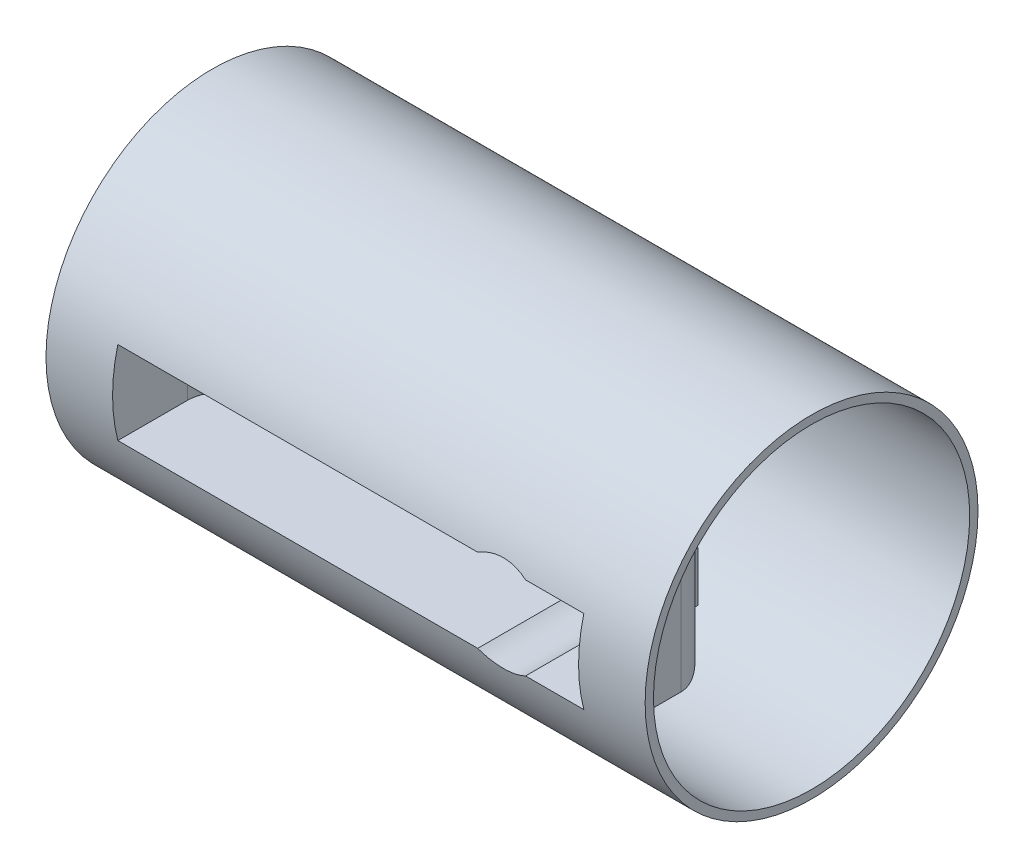
SolidWorks part; units mm, degrees
material "ABS PC"
ref_plane "前视" through (0, 0, 0) normal (0, 0, 1) x (1, 0, 0)
ref_plane "上视" through (0, 0, 0) normal (0, 1, 0) x (1, 0, 0)
ref_plane "右视" through (0, 0, 0) normal (1, 0, 0) x (0, 0, -1)
sketch "草图1" plane through (0, 0, 0) normal (0, 1, 0) x (1, 0, 0)
  line L1 (0, 0) -> (-300, 0)
  line L2 (0, 0) -> (0, -100)
  line L3 (0, -100) -> (-300, -100)
  line L4 (-300, 0) -> (-300, -100)
revolve "旋转1" add sketch "草图1" angle 360 about L1
sketch "草图2" plane through (0, 0, 0) normal (1, 0, 0) x (0, 0, -1)
  circle A0 centre (0, 0) radius 95
extrude "切除-拉伸1" cut sketch "草图2" against normal through all
sketch "草图5" plane through (0, 0, 0) normal (1, 0, 0) x (0, 0, -1)
  circle A0 centre (0, 0) radius 95
  circle A1 centre (0, 0) radius 100
extrude "凸台-拉伸1" add sketch "草图5" along normal blind 60
ref_plane "基准面1" through (0, 0, 100) normal (0, 0, 1) x (1, 0, 0)
sketch "草图6" plane through (0, 0, 100) normal (0, 0, 1) x (1, 0, 0)
  line L0 (60, -100) -> (60, 100) construction
  line L1 (20, 25) -> (-260, 25)
  line L2 (20, 25) -> (20, -25)
  line L3 (20, -25) -> (-260, -25)
  line L4 (-260, 25) -> (-260, -25)
  line L5 (-300, 100) -> (-300, -100) construction
  line L6 (60, 100) -> (-300, 100) construction
  line L7 (-300, -100) -> (60, -100) construction
  dimension "D1" = 40
  dimension "D2" = 40
  dimension "D3" = 75
  dimension "D4" = 75
  dimension "D5" = 50
extrude "切除-拉伸2" cut sketch "草图6" against normal blind 10
sketch "草图9" plane through (20, 0, 0) normal (-1, 0, 0) x (0, 0, 1)
  line L1 (88.3176, 35) -> (88.3176, -35)
  arc A1 (88.3176, -35) -> (88.3176, 35) centre (0, 0) ccw
extrude "凸台-拉伸3" add sketch "草图9" against normal blind 10 and the other way blind 290
sketch "草图14" plane through (0, 0, 88.3176) normal (0, 0, -1) x (-1, 0, 0)
  line L1 (270, -35) -> (-30, -35)
  line L2 (270, -35) -> (270, 35)
  line L3 (270, 35) -> (-30, 35)
  line L4 (-30, -35) -> (-30, 35)
extrude "凸台-拉伸5" add sketch "草图14" along normal blind 60
sketch "草图13" plane through (0, 0, 100) normal (0, 0, 1) x (1, 0, 0)
  line L1 (-260, 25) -> (20, 25)
  line L2 (-260, 25) -> (-260, -25)
  line L3 (-260, -25) -> (20, -25)
  line L4 (20, 25) -> (20, -25)
extrude "切除-拉伸3" cut sketch "草图13" against normal blind 65
fillet "圆角1" radius 20 6 edges at (-120, -35, 28.3176) (30, 0, 28.3176) (-120, 35, 28.3176) (-270, 0, 28.3176) (-260, 0, 35) (20, 0, 35)
sketch "草图15" plane through (0, 0, 28.3176) normal (0, 0, -1) x (-1, 0, 0)
  line L0 (-10, 15) -> (-10, -15) construction
  line L5 (-4.9318, 10) -> (-4.9318, -10)
  line L6 (31, 15) -> (31.0682, 10)
  line L7 (31.0682, -10) -> (31, -15)
  line L8 (-4.9318, 10) -> (31.0682, 10)
  line L10 (-10, 15) -> (31, 15)
  line L12 (-4.9318, -10) -> (31.0682, -10)
  line L13 (-10, -10) -> (-10, -15)
  line L14 (-10, -15) -> (31, -15)
  line L16 (-10, 15) -> (-10, 10)
  line L21 (-10, -10) -> (-10, -15)
  line L23 (-10, 15) -> (-4.9318, 15)
  line L24 (-10, 15) -> (-10, -15)
  line L25 (-10, -15) -> (-4.9318, -15)
  line L30 (-10, 10) -> (-10, -10)
  dimension "D1" = 5
  dimension "D2" = 5
  dimension "D3" = 41
  dimension "D4" = 41
  dimension "D5" = 36
  dimension "D6" = 36
extrude "凸台-拉伸6" add sketch "草图15" along normal blind 10
sketch "草图16" plane through (0, 0, 28.3176) normal (0, 0, -1) x (-1, 0, 0)
  line L0 (-4.9318, 10) -> (-4.9318, -10) construction
  line L1 (-4.9318, 10) -> (31.0682, 10)
  line L2 (-4.9318, 10) -> (-4.9318, -10)
  line L3 (-4.9318, -10) -> (31.0682, -10)
  line L4 (31.0682, 10) -> (31.0682, -10)
extrude "切除-拉伸4" cut sketch "草图16" against normal blind 10
ref_plane "基准面2" through (-31.0682, -10, 35) normal (0, -1, 0) x (-1, 0, 0)
sketch "草图17" plane through (0, 0, 35) normal (0, 0, -1) x (-1, 0, 0)
  line L0 (-4.9318, 0) -> (49995.0682, 0) construction
  line L1 (-4.9318, 10) -> (-4.9318, -10) construction
  circle A0 centre (29.4, 0) radius 28.835
  point P4 (-4.9318, 0)
  dimension "D2" = 57.67
  dimension "D1" = 29.4
extrude "切除-拉伸5" cut sketch "草图17" against normal through all
